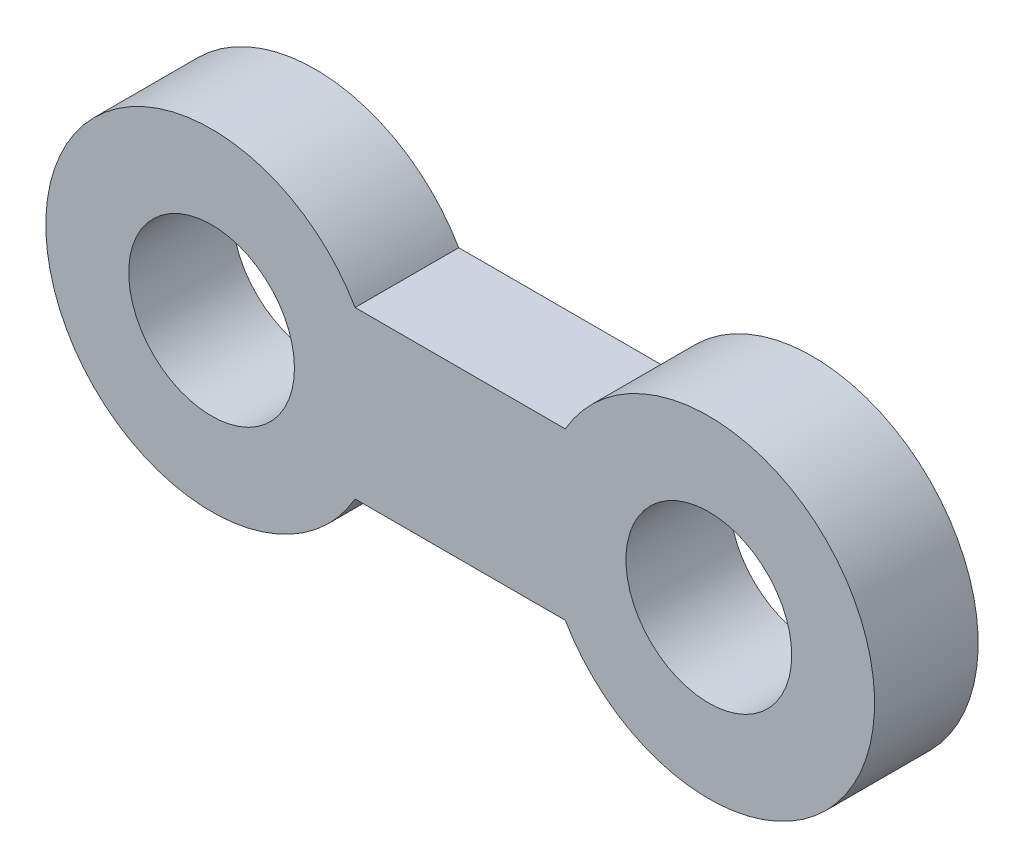
SolidWorks part; units mm, degrees
material "Acrylic (Medium-high impact)"
ref_plane "Front Plane" through (0, 0, 0) normal (0, 0, 1) x (1, 0, 0)
ref_plane "Top Plane" through (0, 0, 0) normal (0, 1, 0) x (1, 0, 0)
ref_plane "Right Plane" through (0, 0, 0) normal (1, 0, 0) x (0, 0, -1)
sketch "Sketch1" plane through (0, 0, 0) normal (0, 0, 1) x (1, 0, 0)
  line L0 (0, 2.54) -> (15.24, 2.54) construction
  line L1 (0, 0) -> (15.24, 0)
  line L2 (0, 0) -> (0, 5.08)
  line L3 (0, 5.08) -> (15.24, 5.08)
  line L4 (15.24, 0) -> (15.24, 5.08)
  line L5 (7.62, 5.08) -> (7.62, 0) construction
  circle A0 centre (0, 2.54) radius 5.08
  circle A1 centre (15.24, 2.54) radius 5.08
  dimension "D3" = 10.16
  dimension "D4" = 10.16
  dimension "D1" = 15.24
  dimension "D2" = 5.08
extrude "Boss-Extrude1" add sketch "Sketch1" along normal blind 3.175 contours L3 A0 L1 L2 | L1 A0 L3 L2 | A1 L3 A0 L1 | L3 A1 L1 L4 | L1 A1 L3 L4
sketch "Sketch2" plane through (0, 0, 3.175) normal (0, 0, 1) x (1, 0, 0)
  line L0 (-5.08, 2.54) -> (20.32, 2.54) construction
  line L1 (0, 7.62) -> (0, -2.54) construction
  line L2 (15.24, 7.62) -> (15.24, -2.54) construction
  arc A0 (4.3994, 5.08) -> (4.3994, 0) centre (0, 2.54) ccw construction
  arc A1 (10.8406, 0) -> (10.8406, 5.08) centre (15.24, 2.54) ccw construction
  circle A2 centre (0, 2.54) radius 2.54
  circle A4 centre (15.24, 2.54) radius 2.54
  dimension "D1" = 5.08
  dimension "D2" = 5.08
extrude "Cut-Extrude1" cut sketch "Sketch2" against normal through all
equation "\"hole-size\"=0.2"
equation "\"D1@Sketch2\"=\"hole-size\""
equation "\"D2@Sketch2\"=\"hole-size\""
